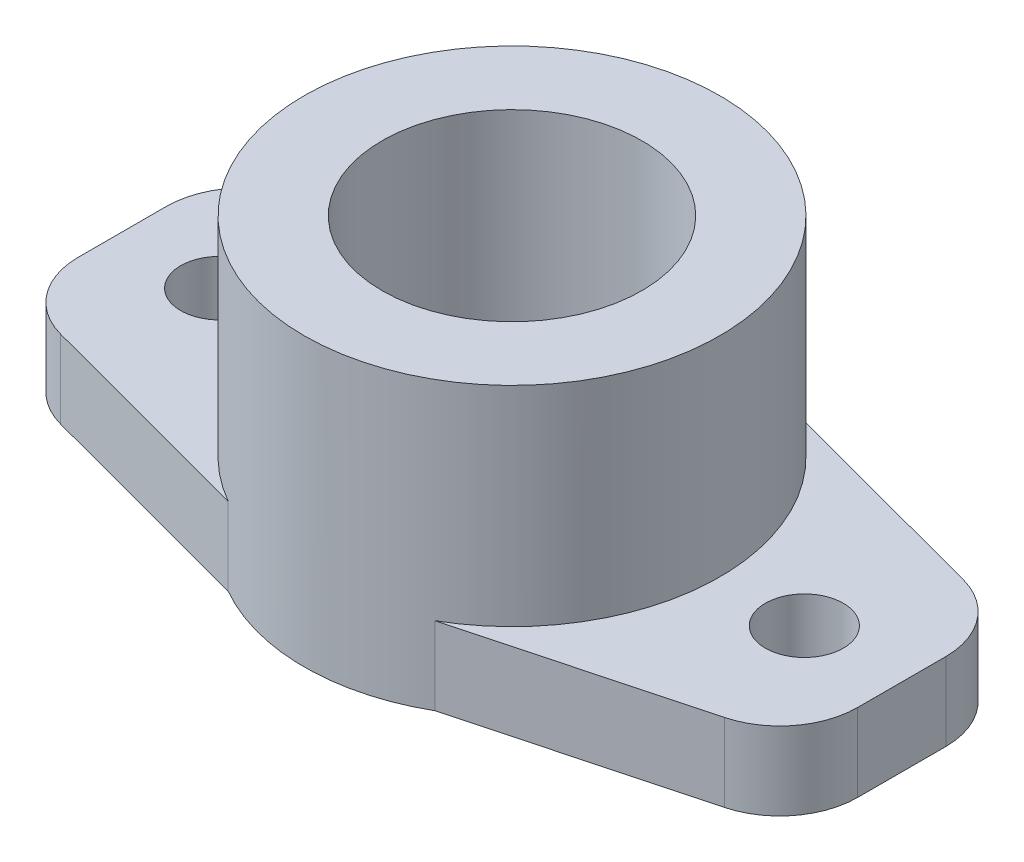
SolidWorks part; units mm, degrees
ref_plane "Front Plane" through (0, 0, 0) normal (0, 0, 1) x (1, 0, 0)
ref_plane "Top Plane" through (0, 0, 0) normal (0, 1, 0) x (1, 0, 0)
ref_plane "Right Plane" through (0, 0, 0) normal (1, 0, 0) x (0, 0, -1)
sketch "Sketch2" plane through (0, 0, 0) normal (0, 1, 0) x (1, 0, 0)
  line L0 (0, 0) -> (15, 0) construction
  line L1 (30, 4) -> (30, 12)
  line L2 (30, 16) -> (15, 16) construction
  line L3 (0, 12) -> (0, 4)
  line L4 (15, 16) -> (15, 0) construction
  line L5 (30, 8) -> (0, 8) construction
  line L6 (18.9834, 14.9378) -> (30, 12)
  line L7 (18.9834, 1.0622) -> (30, 4)
  line L8 (11.0166, 1.0622) -> (0, 4)
  line L9 (11.0166, 14.9378) -> (0, 12)
  line L10 (15, 16) -> (0, 16) construction
  line L11 (0, 16) -> (0, 12) construction
  line L12 (30, 12) -> (30, 16) construction
  line L13 (15, 0) -> (30, 0) construction
  line L14 (30, 0) -> (30, 4) construction
  line L15 (0, 4) -> (0, 0) construction
  line L16 (15, 16) -> (11.0166, 14.9378) construction
  line L17 (15, 16) -> (18.9834, 14.9378) construction
  line L18 (15, 0) -> (11.0166, 1.0622) construction
  line L19 (15, 0) -> (18.9834, 1.0622) construction
  line L20 (22.5, 0) -> (22.5, 16) construction
  line L21 (22.5, 0) -> (30, 0) construction
  line L22 (30, 0) -> (26.25, 0) construction
  line L23 (26.25, 0) -> (26.25, 16) construction
  circle A0 centre (15, 8) radius 5
  arc A1 (11.0166, 1.0622) -> (18.9834, 1.0622) centre (15, 8) ccw
  arc A2 (11.0166, 14.9378) -> (7, 8) centre (15, 8) ccw construction
  circle A3 centre (15, 8) radius 8 construction
  arc A4 (7, 8) -> (11.0166, 1.0622) centre (15, 8) ccw construction
  arc A5 (18.9834, 1.0622) -> (23, 8) centre (15, 8) ccw construction
  arc A6 (18.9834, 14.9378) -> (11.0166, 14.9378) centre (15, 8) ccw
  arc A7 (23, 8) -> (18.9834, 14.9378) centre (15, 8) ccw construction
  circle A8 centre (26.25, 8) radius 1.5
  circle A9 centre (3.75, 8) radius 1.5
  dimension "D1" = 10
  dimension "D6" = 3
  dimension "D3" = 16
  dimension "D4" = 30
  dimension "D5" = 4
  dimension "D2" = 3
extrude "Boss-Extrude1" add sketch "Sketch2" along normal blind 3
fillet "Fillet1" radius 3 4 edges at (0, 1.5, -4) (0, 1.5, -12) (30, 1.5, -12) (30, 1.5, -4)
sketch "Sketch3" plane through (0, 3, 0) normal (0, 1, 0) x (1, 0, 0)
  circle A0 centre (15, 8) radius 8
  circle A1 centre (15, 8) radius 5
extrude "Boss-Extrude2" add sketch "Sketch3" along normal blind 8.04
